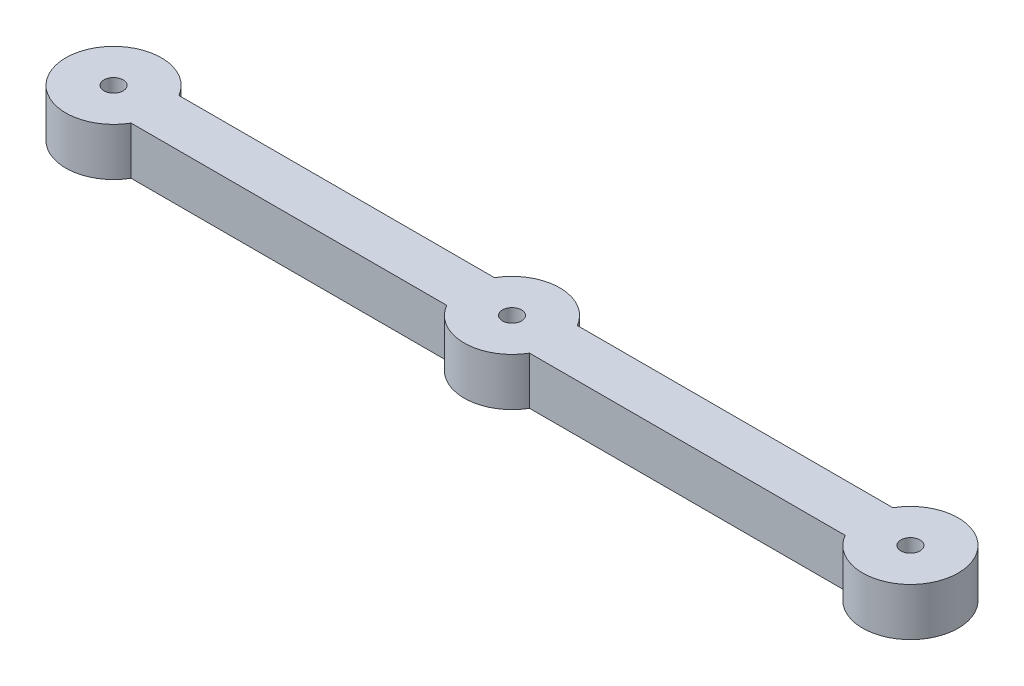
SolidWorks part; units mm, degrees
other "标注1"
sketch "草图3" plane through (-22.25, 4, -10) normal (-0.231, 0.6469, -0.7268) x (-0.9696, -0.2151, 0.1167)
ref_plane "前视基准面" through (0, 0, 0) normal (0, 0, 1) x (1, 0, 0)
ref_plane "上视基准面" through (0, 0, 0) normal (0, 1, 0) x (1, 0, 0)
ref_plane "右视基准面" through (0, 0, 0) normal (1, 0, 0) x (0, 0, -1)
other "Configuration Table"
sketch "草图4" plane through (0, 0, 0) normal (0, 1, 0) x (1, 0, 0)
  line L1 (-25, 1.5) -> (25, 1.5)
  line L2 (-25, 1.5) -> (-25, -1.5)
  line L3 (-25, -1.5) -> (25, -1.5)
  line L4 (25, 1.5) -> (25, -1.5)
  line L5 (-25, 1.5) -> (25, -1.5) construction
  line L6 (-25, -1.5) -> (25, 1.5) construction
  circle A3 centre (0, 0) radius 3
  circle A4 centre (25, 0) radius 3
  circle A5 centre (-25, 0) radius 3
  point P0 (0, 0)
  point P13 (0, 0)
  dimension "D1" = 3
  dimension "D2" = 50
  dimension "D3" = 6
extrude "凸台-拉伸1" add sketch "草图4" along normal blind 3 contours A5 | L1 L4 L3 L2 | A3 | A4
sketch "草图5" plane through (0, 0, 0) normal (0, -1, 0) x (1, 0, 0)
  circle A0 centre (-25, 0) radius 1.5
  circle A1 centre (0, 0) radius 1.5
  circle A2 centre (25, 0) radius 1.5
  arc A3 (-22.4019, 1.5) -> (-22.4019, -1.5) centre (-25, 0) ccw construction
  arc A4 (2.5981, 1.5) -> (-2.5981, 1.5) centre (0, 0) ccw construction
  arc A5 (22.4019, -1.5) -> (22.4019, 1.5) centre (25, 0) ccw construction
  dimension "D1" = 3
extrude "切除-拉伸1" cut sketch "草图5" against normal blind 1.2
sketch "草图6" plane through (0, 0, 0) normal (0, -1, 0) x (-1, 0, 0)
  circle A0 centre (0, 0) radius 0.6
  circle A1 centre (-25, 0) radius 0.6
  circle A2 centre (25, 0) radius 0.6
  circle A3 centre (25, 0) radius 1.5 construction
  circle A4 centre (0, 0) radius 1.5 construction
  circle A5 centre (-25, 0) radius 1.5 construction
  dimension "D1" = 1.2
extrude "切除-拉伸2" cut sketch "草图6" against normal through all
